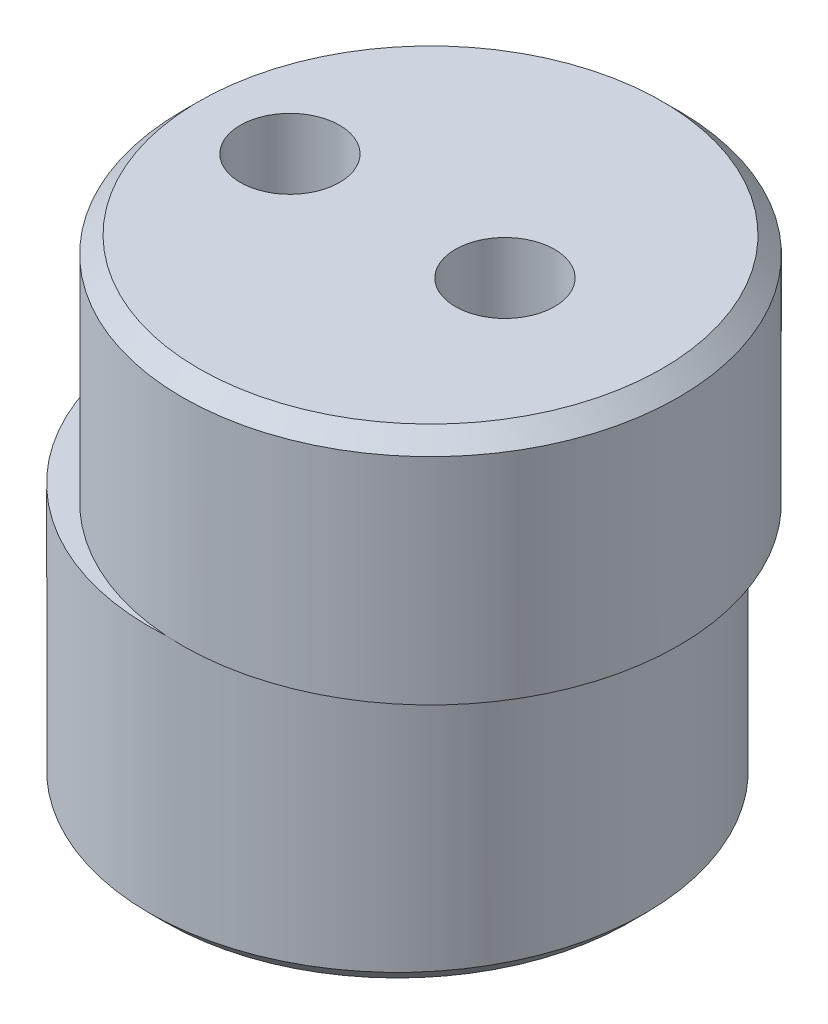
SolidWorks part; units mm, degrees
material "Cast Stainless Steel"
ref_plane "Front Plane" through (0, 0, 0) normal (0, 0, 1) x (1, 0, 0)
ref_plane "Top Plane" through (0, 0, 0) normal (0, 1, 0) x (1, 0, 0)
ref_plane "Right Plane" through (0, 0, 0) normal (1, 0, 0) x (0, 0, -1)
sketch "Sketch1" plane through (0, 0, 0) normal (0, 1, 0) x (1, 0, 0)
  circle A0 centre (0, 0) radius 7.5
  dimension "Outer Diameter" = 15
extrude "Boss-Extrude1" add sketch "Sketch1" along normal blind 8
sketch "Sketch2" plane through (0, 8, 0) normal (0, 1, 0) x (1, 0, 0)
  line L0 (0, 0) -> (1, 0) construction
  circle A0 centre (1, 0) radius 7.5
  dimension "First Cycloid Base" = 15
  dimension "Eccentricity" = 1
extrude "Boss-Extrude2" add sketch "Sketch2" along normal blind 7
sketch "Sketch3" plane through (0, 0, 0) normal (0, -1, 0) x (1, 0, 0)
  line L0 (3.25, 0) -> (-3.25, 0) construction
  circle A0 centre (-3.25, 0) radius 1.5
  circle A1 centre (3.25, 0) radius 1.5
  point P4 (0, 0)
  dimension "D1" = 3
  dimension "D2" = 6.5
extrude "Cut-Extrude1" cut sketch "Sketch3" against normal through all
chamfer "Chamfer1" distance 0.5 angle 45 2 edges at (0, 0, 7.5) (1, 15, 7.5)
equation "\"Outer Diameter\"= 15"
equation "\"Outer Diameter@Sketch1\"=\"Outer Diameter\""
equation "\"Bottom Thickness\"= 8"
equation "\"D1@Boss-Extrude1\"=\"Bottom Thickness\""
equation "\"Bottom Cycloid Diameter\"= 15"
equation "\"First Cycloid Base@Sketch2\"=\"Bottom Cycloid Diameter\""
equation "\"Bottom Cycloid Thickness\"= 7"
equation "\"D1@Boss-Extrude2\"=\"Bottom Cycloid Thickness\""
equation "\"Eccentricity\"= 1"
equation "\"Top Cycloid Diameter\"= 10"
equation "\"Top Base Diameter\"= 10"
equation "\"Top Base Thickness\"= 5"
equation "\"E\"= 1"
equation "\"Eccentricity@Sketch2\"=\"E\""
